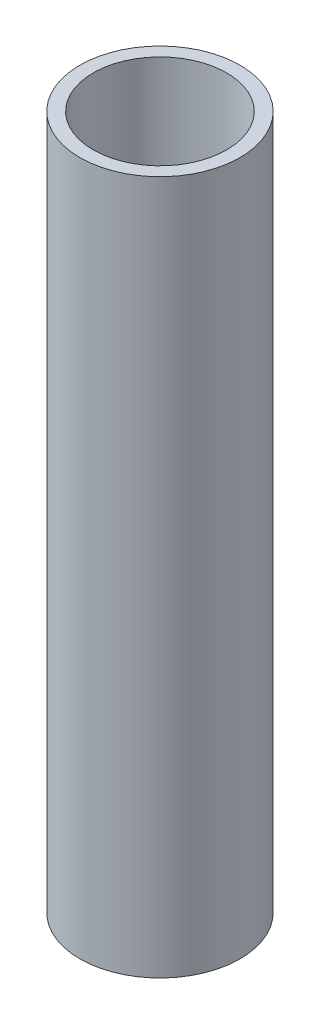
SolidWorks part; units mm, degrees
material "6061-T6 (SS)"
ref_plane "Front Plane" through (0, 0, 0) normal (0, 0, 1) x (1, 0, 0)
ref_plane "Top Plane" through (0, 0, 0) normal (0, 1, 0) x (1, 0, 0)
ref_plane "Right Plane" through (0, 0, 0) normal (1, 0, 0) x (0, 0, -1)
sketch "Sketch1" plane through (0, 0, 0) normal (0, 1, 0) x (1, 0, 0)
  circle A0 centre (0, 0) radius 4.7625
  circle A1 centre (0, 0) radius 3.9688
  dimension "D1" = 9.525
  dimension "D2" = 7.9375
extrude "Boss-Extrude1" add sketch "Sketch1" along normal blind 41.275
